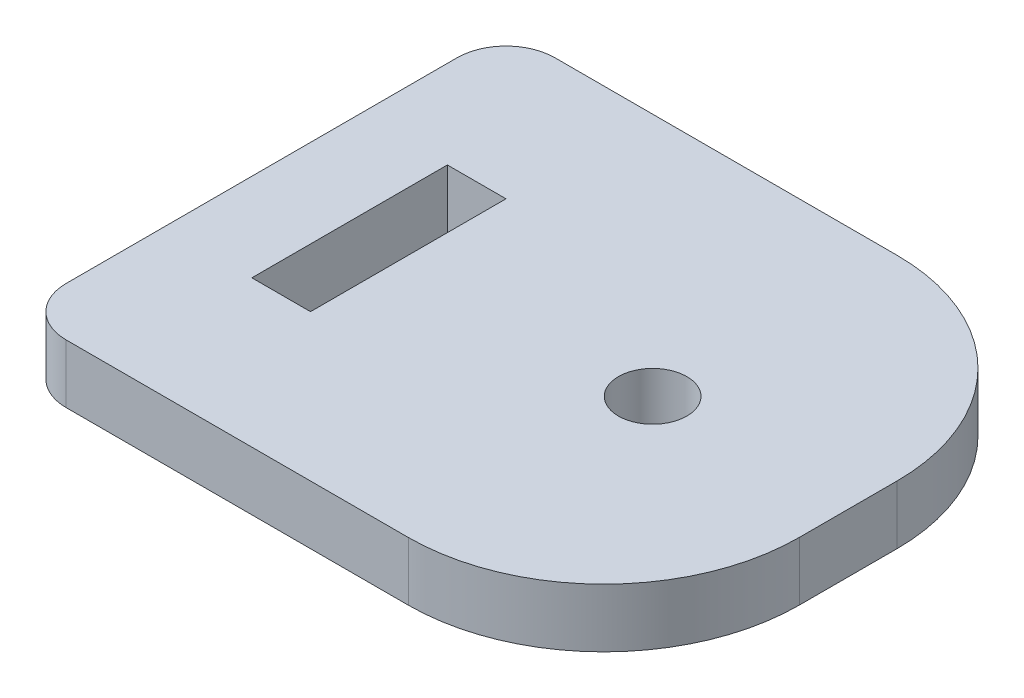
SolidWorks part; units mm, degrees
ref_plane "Front Plane" through (0, 0, 0) normal (0, 0, 1) x (1, 0, 0)
ref_plane "Top Plane" through (0, 0, 0) normal (0, 1, 0) x (1, 0, 0)
ref_plane "Right Plane" through (0, 0, 0) normal (1, 0, 0) x (0, 0, -1)
sketch "Sketch1" plane through (0, 0, 0) normal (0, 1, 0) x (1, 0, 0)
  line L1 (-12.5, -12.5) -> (5, -12.5)
  line L2 (-15, -10) -> (-15, 10)
  line L3 (-12.5, 12.5) -> (5, 12.5)
  line L4 (15, -2.5) -> (15, 2.5)
  line L5 (-15, -12.5) -> (15, 12.5) construction
  line L6 (-15, 12.5) -> (15, -12.5) construction
  line L7 (-10.5, -5) -> (-7.5, -5)
  line L8 (-10.5, -5) -> (-10.5, 5)
  line L9 (-10.5, 5) -> (-7.5, 5)
  line L10 (-7.5, -5) -> (-7.5, 5)
  line L11 (-10.5, -5) -> (-7.5, 5) construction
  line L12 (-10.5, 5) -> (-7.5, -5) construction
  arc A0 (-12.5, -12.5) -> (-15, -10) centre (-12.5, -10) cw
  arc A1 (-12.5, 12.5) -> (-15, 10) centre (-12.5, 10) ccw
  arc A2 (15, -2.5) -> (5, -12.5) centre (5, -2.5) cw
  arc A3 (15, 2.5) -> (5, 12.5) centre (5, 2.5) ccw
  circle A4 centre (5, 0) radius 1.75
  point P0 (0, 0)
  point P18 (-9, 0)
  dimension "D3" = 2.5
  dimension "D4" = 10
  dimension "D9" = 3.5
  dimension "D1" = 25
  dimension "D2" = 30
  dimension "D5" = 3
  dimension "D6" = 4.5
  dimension "D7" = 10
  dimension "D8" = 20
extrude "Boss-Extrude1" add sketch "Sketch1" along normal blind 3
